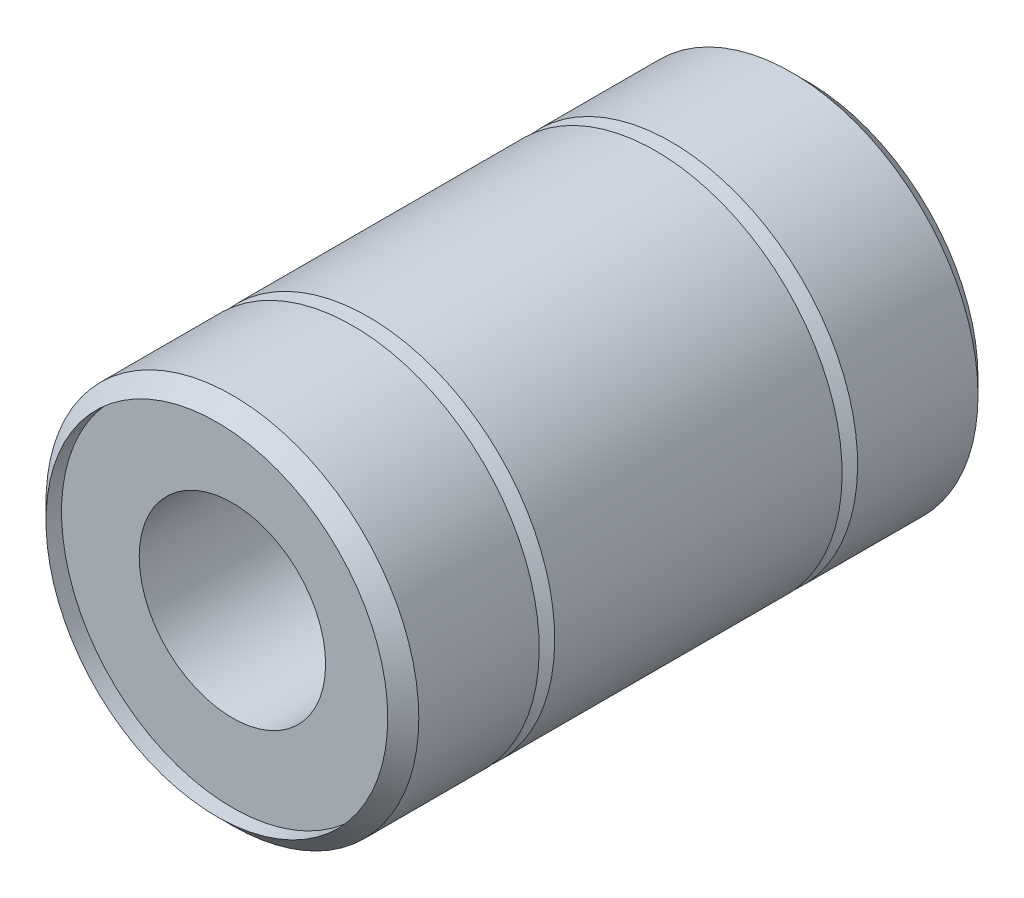
SolidWorks part; units mm, degrees
ref_plane "정면" through (0, 0, 0) normal (0, 0, 1) x (1, 0, 0)
ref_plane "윗면" through (0, 0, 0) normal (0, 1, 0) x (1, 0, 0)
ref_plane "우측면" through (0, 0, 0) normal (1, 0, 0) x (0, 0, -1)
sketch "스케치1" plane through (0, 0, 0) normal (0, 0, 1) x (1, 0, 0)
  circle A0 centre (0, 0) radius 6
  circle A1 centre (0, 0) radius 3
  dimension "D1" = 12
  dimension "D2" = 6
extrude "보스-돌출1" add sketch "스케치1" along normal mid plane 19
chamfer "모따기1" distance 0.5 angle 45 2 edges at (6, 0, -9.5) (6, 0, 9.5)
sketch "스케치2" plane through (0, 0, 9.5) normal (0, 0, 1) x (1, 0, 0)
  circle A1 centre (0, 0) radius 5.5
  circle A2 centre (0, 0) radius 5.5
  dimension "D1" = 0
extrude "컷-돌출1" cut sketch "스케치2" against normal blind 0.5
mirror "대칭 복사1" about plane through (0, 0, 0) normal (0, 0, 1) of "컷-돌출1"
sketch "스케치3" plane through (0, 0, 0) normal (1, 0, 0) x (0, 0, -1)
  line L0 (0, 0) -> (0, 6) construction
  line L1 (9, 6) -> (-9, 6) construction
  line L2 (-4.625, 6) -> (4.625, 6) construction
  line L3 (-4.625, 6) -> (-5.125, 6)
  line L4 (4.625, 6) -> (5.125, 6)
  line L5 (-5.125, 6) -> (-4.875, 5.567)
  line L6 (5.125, 6) -> (4.875, 5.567)
  line L7 (-4.875, 5.567) -> (-4.625, 6)
  line L8 (4.875, 5.567) -> (4.625, 6)
  line L9 (-9, 0) -> (9, 0) construction
  line L10 (-9, -6) -> (-9, 6) construction
  line L11 (9, 6) -> (9, -6) construction
  circle A0 centre (-4.875, 5.8557) radius 0.1443 construction
  dimension "D1" = 10
  dimension "D2" = 0.5
revolve "컷-회전1" cut sketch "스케치3" angle 360 about L9
